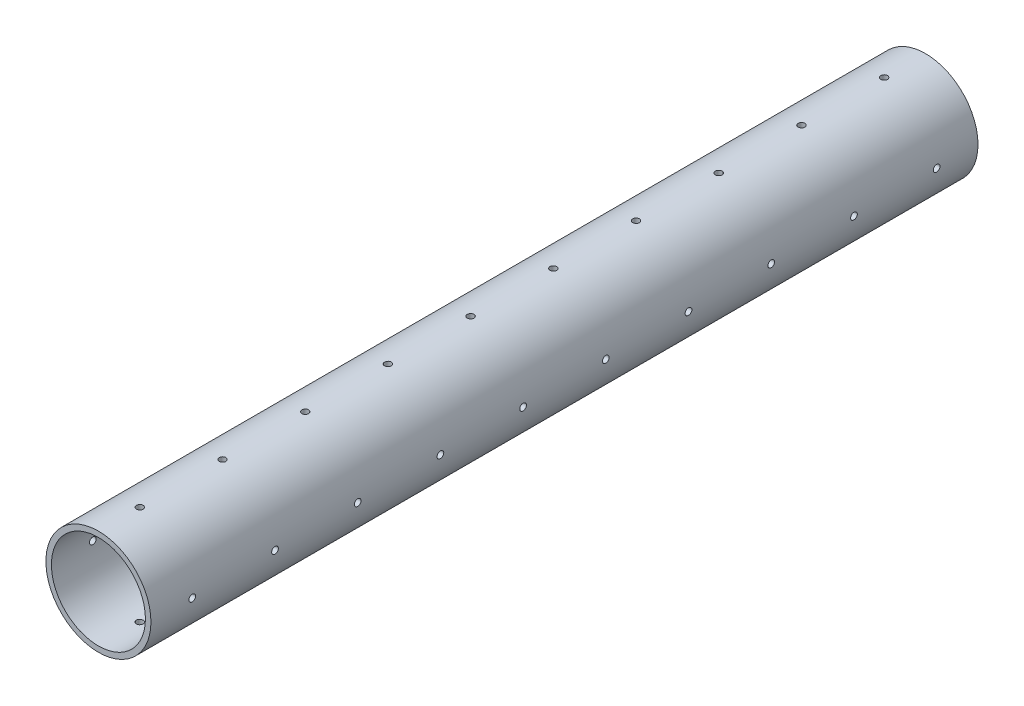
SolidWorks part; units mm, degrees
material "7075-T6 (SN)"
ref_plane "Front" through (0, 0, 0) normal (0, 0, 1) x (1, 0, 0)
ref_plane "Top" through (0, 0, 0) normal (0, 1, 0) x (1, 0, 0)
ref_plane "Right" through (0, 0, 0) normal (1, 0, 0) x (0, 0, -1)
sketch "Sketch1" plane through (0, 0, 0) normal (0, 0, 1) x (1, 0, 0)
  circle A0 centre (0, 0) radius 15.875
  circle A1 centre (0, 0) radius 14.2108
  dimension "D1" = 31.75
  dimension "D2" = 28.4216
extrude "Boss-Extrude1" add sketch "Sketch1" along normal blind 250
sketch "Sketch2" plane through (0, 0, 0) normal (0, 1, 0) x (1, 0, 0)
  line L0 (0, 0) -> (0, -250) construction
  line L1 (-15.875, -250) -> (15.875, -250) construction
  line L2 (14.2108, 0) -> (-14.2108, 0) construction
  line L3 (-15.875, -125) -> (15.875, -125) construction
  line L4 (-15.875, 0) -> (-15.875, -250) construction
  line L5 (15.875, -250) -> (15.875, 0) construction
  circle A0 centre (0, -12.5) radius 1.0125
  circle A1 centre (0, -312.5) radius 1.0125
  circle A2 centre (0, -37.5) radius 1.0125
  circle A3 centre (0, -62.5) radius 1.0125
  circle A4 centre (0, -87.5) radius 1.0125
  circle A5 centre (0, -112.5) radius 1.0125
  circle A6 centre (0, -137.5) radius 1.0125
  circle A7 centre (0, -162.5) radius 1.0125
  circle A8 centre (0, -187.5) radius 1.0125
  circle A9 centre (0, -212.5) radius 1.0125
  circle A10 centre (0, -237.5) radius 1.0125
  circle A11 centre (0, -262.5) radius 1.0125
  circle A12 centre (0, -287.5) radius 1.0125
  circle A13 centre (0, -337.5) radius 1.0125
  circle A20 centre (0, -312.5) radius 1.0125 [skipped]
  circle A21 centre (0, -337.5) radius 1.0125 [skipped]
  circle A22 centre (0, -362.5) radius 1.0125 [skipped]
  circle A23 centre (0, -387.5) radius 1.0125 [skipped]
  circle A24 centre (0, -412.5) radius 1.0125 [skipped]
  circle A25 centre (0, -437.5) radius 1.0125 [skipped]
  circle A26 centre (0, -462.5) radius 1.0125 [skipped]
  dimension "D1" = 2.025
  dimension "D2" = 12.5
  dimension "D3" = 2.025
  dimension "D4" = 25
  dimension "D7" = 25
  dimension "D6" = 25
  dimension "D5" = 18
extrude "Cut-Extrude1" cut sketch "Sketch2" against normal up to surface and the other way up to surface up to face at (15.875, 0, 250) other way up to face at (15.875, 0, 250)
sketch "Sketch3" plane through (0, 0, 0) normal (1, 0, 0) x (0, 0, -1)
  line L0 (0, 0) -> (-250, 0) construction
  line L1 (-250, 15.875) -> (-250, -15.875) construction
  line L2 (0, -14.2108) -> (0, 14.2108) construction
  circle A0 centre (-12.5, 0) radius 1.0125
  circle A2 centre (-37.5, 0) radius 1.0125
  circle A3 centre (-62.5, 0) radius 1.0125
  circle A4 centre (-87.5, 0) radius 1.0125
  circle A5 centre (-112.5, 0) radius 1.0125
  circle A6 centre (-137.5, 0) radius 1.0125
  circle A7 centre (-162.5, 0) radius 1.0125
  circle A8 centre (-187.5, 0) radius 1.0125
  circle A9 centre (-212.5, 0) radius 1.0125
  circle A10 centre (-237.5, 0) radius 1.0125
  circle A11 centre (-262.5, 0) radius 1.0125
  circle A12 centre (-287.5, 0) radius 1.0125
  circle A20 centre (-312.5, 0) radius 1.0125 [skipped]
  circle A21 centre (-337.5, 0) radius 1.0125 [skipped]
  circle A22 centre (-362.5, 0) radius 1.0125 [skipped]
  circle A23 centre (-387.5, 0) radius 1.0125 [skipped]
  circle A24 centre (-412.5, 0) radius 1.0125 [skipped]
  circle A25 centre (-437.5, 0) radius 1.0125 [skipped]
  circle A26 centre (-462.5, 0) radius 1.0125 [skipped]
  dimension "D2" = 2.025
  dimension "D3" = 12.5
  dimension "D5" = 2.025
  dimension "D6" = 25
  dimension "D7" = 18
extrude "Cut-Extrude2" cut sketch "Sketch3" against normal up to surface and the other way up to surface up to face at (0.2306, -15.8733, 236.5141) other way up to face at (0.2306, -15.8733, 236.5141)
